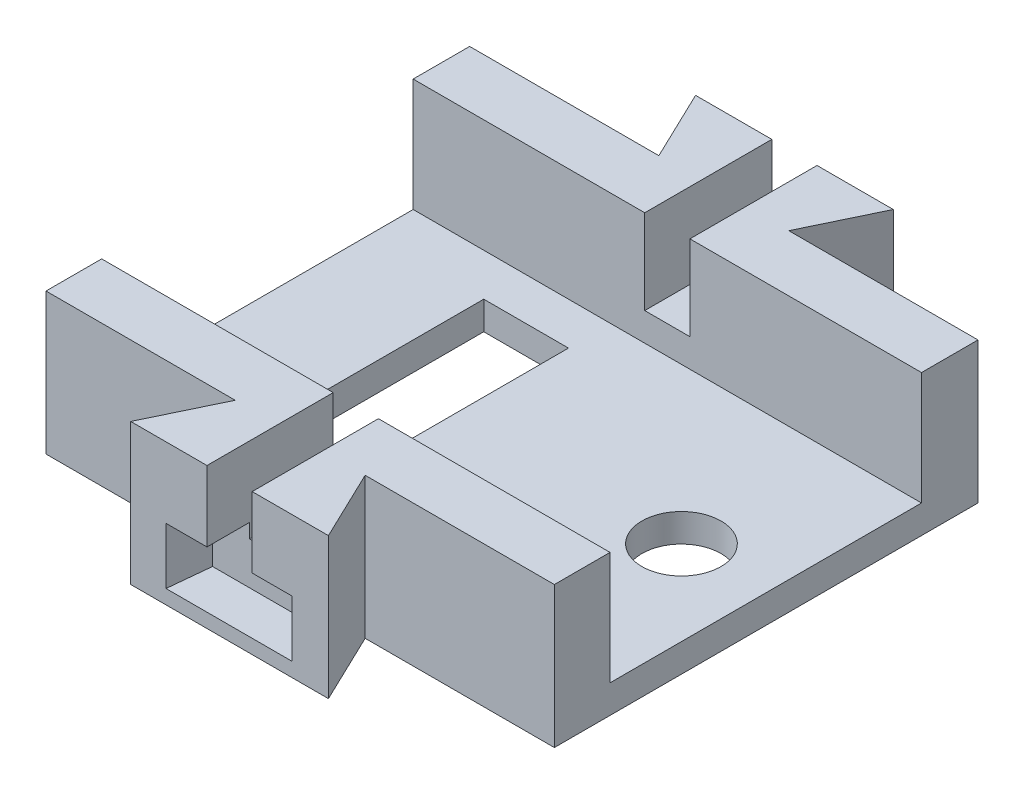
SolidWorks part; units mm, degrees
ref_plane "Front Plane" through (0, 0, 0) normal (0, 0, 1) x (1, 0, 0)
ref_plane "Top Plane" through (0, 0, 0) normal (0, 1, 0) x (1, 0, 0)
ref_plane "Right Plane" through (0, 0, 0) normal (1, 0, 0) x (0, 0, -1)
sketch "Sketch1" plane through (0, 0, 0) normal (0, 1, 0) x (1, 0, 0)
  line L1 (-59.3211, 124.9321) -> (120.6789, 124.9321)
  line L2 (-59.3211, 124.9321) -> (-59.3211, -25.0679)
  line L3 (-59.3211, -25.0679) -> (120.6789, -25.0679)
  line L4 (120.6789, 124.9321) -> (120.6789, -25.0679)
  line L5 (-19.3211, 9.9321) -> (10.6789, 9.9321)
  line L6 (-19.3211, 9.9321) -> (-19.3211, 89.9321)
  line L7 (-19.3211, 89.9321) -> (10.6789, 89.9321)
  line L8 (10.6789, 9.9321) -> (10.6789, 89.9321)
  dimension "D1" = 35
  dimension "D2" = 35
  dimension "D3" = 40
extrude "Boss-Extrude1" add sketch "Sketch1" along normal blind 50 contours L2 L3 L4 L1
shell "Shell1" thickness 20
sketch "Sketch3" plane through (0, 0, 0) normal (0, -1, 0) x (-1, 0, 0)
sketch "Sketch4" plane through (0, 50, 0) normal (0, 1, 0) x (1, 0, 0)
  line L0 (-39.3211, -5.0679) -> (-39.3211, 104.9321)
  line L1 (-39.3211, 104.9321) -> (30.6789, 104.9321)
  line L2 (30.6789, 104.9321) -> (30.6789, -5.0679)
  line L3 (30.6789, -5.0679) -> (-39.3211, -5.0679)
  line L4 (30.6789, -5.0679) -> (100.6789, -5.0679) construction
extrude "Cut-Extrude1" cut sketch "Sketch4" against normal blind 30
sketch "Sketch5" plane through (0, 0, 0) normal (0, -1, 0) x (1, 0, 0)
  line L0 (30.6789, 25.0679) -> (7.6789, 25.0679)
  line L1 (-59.3211, 25.0679) -> (120.6789, 25.0679) construction
  line L2 (7.6789, 25.0679) -> (-4.3211, 50.0679)
  line L3 (-4.3211, 50.0679) -> (65.6789, 50.0679)
  line L4 (65.6789, 50.0679) -> (53.6789, 25.0679)
  line L5 (53.6789, 25.0679) -> (30.6789, 25.0679)
  line L7 (19.067, 29.7324) -> (61.7771, 29.7324)
  line L8 (61.7771, 29.7324) -> (73.0332, 45.955)
  line L9 (73.0332, 45.955) -> (10.5603, 45.955)
  line L10 (10.5603, 45.955) -> (19.067, 29.7324)
  dimension "D1" = 23
  dimension "D2" = 23
  dimension "D3" = 25
  dimension "D4" = 25
  dimension "D5" = 55
  dimension "D6" = 55
extrude "Boss-Extrude2" add sketch "Sketch5" against normal blind 50 contours L3 L4 L5 L0 L2
sketch "Sketch6" plane through (0, 50, 0) normal (0, 1, 0) x (1, 0, 0)
  line L0 (22.6789, -50.0679) -> (22.6789, -5.0679)
  line L1 (-4.3211, -50.0679) -> (65.6789, -50.0679) construction
  line L2 (-39.3211, -5.0679) -> (100.6789, -5.0679) construction
  line L3 (22.6789, -5.0679) -> (38.6789, -5.0679)
  line L4 (38.6789, -5.0679) -> (38.6789, -50.0679)
  line L5 (38.6789, -50.0679) -> (22.6789, -50.0679)
  dimension "D1" = 15
  dimension "D2" = 15
extrude "Cut-Extrude2" cut sketch "Sketch6" against normal blind 30
ref_plane "Plane1" through (0, 0, -49.9321) normal (0, 0, 1) x (1, 0, 0)
sketch "Sketch7" plane through (0, 0, 0) normal (0, -1, 0) x (-1, 0, 0)
  line L0 (-90.6789, 124.9321) -> (-90.6789, -25.0679) construction
  line L1 (-120.6789, 124.9321) -> (59.3211, 124.9321) construction
  line L2 (-53.6789, -25.0679) -> (-120.6789, -25.0679) construction
  line L3 (-90.6789, 49.9321) -> (-120.6789, 49.9321) construction
  line L4 (-120.6789, -25.0679) -> (-120.6789, 124.9321) construction
  circle A0 centre (-90.6789, 49.9321) radius 10
extrude "Cut-Extrude3" cut sketch "Sketch7" against normal blind 28 contours A0
sketch "Sketch8" plane through (120.6789, 0, 0) normal (1, 0, 0) x (0, 0, -1)
  line L0 (104.9321, 50) -> (104.9321, 10)
  line L1 (-25.0679, 50) -> (124.9321, 50) construction
  line L2 (104.9321, 10) -> (-5.3609, 10)
  line L3 (-5.3609, 10) -> (-5.3609, 50)
  line L4 (-5.3609, 50) -> (104.9321, 50)
extrude "Cut-Extrude4" cut sketch "Sketch8" against normal blind 213
sketch "Sketch9" plane through (0, 0, 0) normal (0, -1, 0) x (1, 0, 0)
  line L0 (49.1131, -66.3474) -> (20.5792, -66.3474)
  line L1 (20.5792, -66.3474) -> (29.8654, -57.0611)
  line L2 (29.8654, -57.0611) -> (58.3993, -57.0611)
  line L3 (58.3993, -57.0611) -> (49.1131, -66.3474)
  line L4 (39.3182, -54.9958) -> (39.3182, -45.201)
  line L5 (39.3182, -45.201) -> (48.6045, -35.9147)
  line L6 (48.6045, -35.9147) -> (58.3993, -35.9147)
  line L7 (58.3993, -35.9147) -> (39.3182, -54.9958)
  line L8 (46.3978, -35.9147) -> (29.8654, -35.9147)
  line L9 (29.8654, -35.9147) -> (20.5792, -45.201)
  line L10 (20.5792, -45.201) -> (37.1116, -45.201)
  line L11 (37.1116, -45.201) -> (46.3978, -35.9147)
extrude "Cut-Extrude5" cut sketch "Sketch9" against normal blind 2 contours L7 L6 L5 L4 | L10 L11 L8 L9 | L0 L1 L2 L3
sketch "Sketch10" plane through (0, 0, 0) normal (0, -1, 0) x (1, 0, 0)
  circle A0 centre (90.6789, -49.9321) radius 14
  circle A1 centre (90.6789, -49.9321) radius 10 construction
extrude "Cut-Extrude6" cut sketch "Sketch10" against normal blind 10
sketch "Sketch11" plane through (0, 0, 0) normal (0, -1, 0) x (-1, 0, 0)
  line L0 (4.3211, 94.9321) -> (4.3211, 89.9321) construction
  line L1 (24.3211, 94.9321) -> (-15.6789, 94.9321)
  line L2 (24.3211, 94.9321) -> (24.3211, 4.9321)
  line L3 (24.3211, 4.9321) -> (-15.6789, 4.9321)
  line L4 (-15.6789, 94.9321) -> (-15.6789, 4.9321)
  line L5 (-10.6789, 89.9321) -> (19.3211, 89.9321) construction
  line L6 (4.3211, 9.9321) -> (4.3211, 4.9321) construction
  line L7 (19.3211, 9.9321) -> (-10.6789, 9.9321) construction
sketch "Sketch13" plane through (0, 0, 50.0679) normal (0, 0, 1) x (1, 0, 0)
  line L0 (40.9724, 5.0164) -> (40.9724, 25.0164)
  line L1 (40.9724, 25.0164) -> (20.9724, 25.0164)
  line L2 (20.9724, 25.0164) -> (20.9724, 5.0164)
  line L3 (20.9724, 5.0164) -> (40.9724, 5.0164)
  point P4 (0, 0)
  point P5 (0, 0)
  point P6 (0, 0)
  point P8 (0, 0)
extrude "Cut-Extrude10" cut sketch "Sketch13" against normal blind 15
sketch "Sketch14" plane through (0, 0, 0) normal (0, -1, 0) x (-1, 0, 0)
  line L0 (-53.1789, -50.0679) -> (-50.6789, -25.0679)
  line L1 (-50.6789, -25.0679) -> (-10.6789, -25.0679)
  line L2 (-10.6789, -25.0679) -> (-8.1789, -50.0679)
  line L3 (-8.1789, -50.0679) -> (-53.1789, -50.0679)
  line L4 (-50.6789, -25.0679) -> (-53.6789, -25.0679) construction
  line L5 (-7.6789, -25.0679) -> (-10.6789, -25.0679) construction
  line L9 (4.3211, -50.0679) -> (-65.6789, -50.0679) construction
  point P16 (0, 0)
sketch "Sketch16" plane through (0, 25.0164, 0) normal (0, -1, 0) x (1, 0, 0)
  line L0 (9.659, 35.0679) -> (8.159, 50.0679)
  line L1 (8.159, 50.0679) -> (52.7046, 50.0679)
  line L2 (52.7046, 50.0679) -> (51.2046, 35.0679)
  line L3 (51.2046, 35.0679) -> (9.659, 35.0679)
  line L4 (8.159, 50.0679) -> (19.0273, 50.0679) construction
  line L5 (63.5729, 50.0679) -> (52.7046, 50.0679) construction
  line L6 (40.9724, 50.0679) -> (38.6789, 50.0679) construction
  line L7 (22.6789, 35.0679) -> (20.9724, 35.0679) construction
  line L8 (10.6789, 25.0679) -> (8.1789, 50.0679) construction
  point P8 (47.5049, 18.9863)
  point P9 (53.0455, 50.0679)
  point P10 (8.159, 50.0679)
  point P11 (9.5453, 19.9082)
  point P14 (0, 0)
  point P15 (0, 0)
  point P18 (21.8257, 35.0679)
extrude "Cut-Extrude11" cut sketch "Sketch16" along normal blind 20
mirror "Mirror1" about plane through (0, 0, -49.9321) normal (0, 0, 1) of "Boss-Extrude2", "Cut-Extrude2", "Cut-Extrude10", "Cut-Extrude11"
